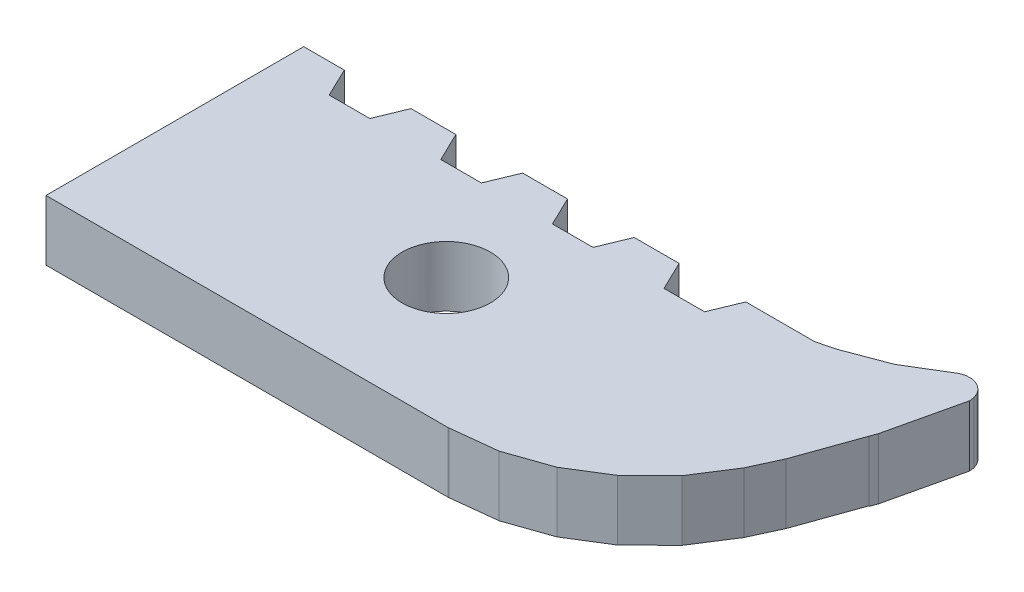
SolidWorks part; units mm, degrees
material "PET"
ref_plane "Front" through (0, 0, 0) normal (0, 0, 1) x (1, 0, 0)
ref_plane "Top" through (0, 0, 0) normal (0, 1, 0) x (1, 0, 0)
ref_plane "Right" through (0, 0, 0) normal (1, 0, 0) x (0, 0, -1)
sketch "Sketch1" plane through (0, 0, 0) normal (0, 1, 0) x (1, 0, 0)
  line L0 (-23.1719, 5.6259) -> (-23.1719, -7.0741)
  line L1 (-23.1719, 5.6259) -> (2.2281, 5.6259)
  line L3 (-23.1719, -7.0741) -> (2.2281, -7.0741)
  line L5 (-23.1719, 5.6259) -> (2.2281, -7.0741) construction
  line L6 (-23.1719, -7.0741) -> (2.2281, 5.6259) construction
  arc A1 (2.2281, 5.6259) -> (2.2281, -7.0741) centre (2.2281, -0.7241) cw
  point P4 (-10.4719, -0.7241)
  dimension "D3" = 12.7
extrude "Boss-Extrude1" add sketch "Sketch1" along normal blind 2.975
sketch "Sketch3" plane through (0, 2.975, 0) normal (0, 1, 0) x (1, 0, 0)
  line L1 (-21.1719, 5.6259) -> (-17.8821, 5.6259)
  line L2 (2.2281, 5.6259) -> (-23.1719, 5.6259) construction
  line L3 (-21.1719, 5.6259) -> (-20.4769, 4.1873)
  line L4 (-20.4769, 4.1873) -> (-18.4769, 4.1873)
  line L5 (-18.4769, 4.1873) -> (-17.8821, 5.6259)
  line L6 (-15.6719, 5.6259) -> (-12.3821, 5.6259)
  line L7 (-10.1719, 5.6259) -> (-6.8821, 5.6259)
  line L8 (-15.6719, 5.6259) -> (-14.9769, 4.1873)
  line L9 (-14.9769, 4.1873) -> (-12.9769, 4.1873)
  line L10 (-12.9769, 4.1873) -> (-12.3821, 5.6259)
  line L11 (-4.6719, 5.6259) -> (-1.3821, 5.6259)
  line L13 (-10.1719, 5.6259) -> (-9.4769, 4.1873)
  line L14 (-9.4769, 4.1873) -> (-7.4769, 4.1873)
  line L15 (-7.4769, 4.1873) -> (-6.8821, 5.6259)
  line L18 (-4.6719, 5.6259) -> (-3.9769, 4.1873)
  line L19 (-3.9769, 4.1873) -> (-1.9769, 4.1873)
  line L20 (-1.9769, 4.1873) -> (-1.3821, 5.6259)
  circle A0 centre (-9.8069, -0.7139) radius 2.175
  line M7 (2.2281, 5.6259) -> (-23.1719, 5.6259)
  dimension "D2" = 4.35
  dimension "D1" = 7.83
  dimension "D5" = 4
  dimension "D6" = 2
extrude "Cut-Extrude1" cut sketch "Sketch3" against normal blind 10 contours L4 L5 L3 M7 | L9 L10 L8 M7 | L14 L15 L13 M7 | L19 L20 L18 M7 | A0
sketch "Sketch4" plane through (0, 2.975, 0) normal (0, 1, 0) x (1, 0, 0)
  line L0 (2.0125, 5.6259) -> (2.8774, 5.8481)
  line L1 (2.2281, 5.6259) -> (-1.3821, 5.6259) construction
  line L2 (2.8774, 5.8481) -> (4.9554, 6.6311)
  line L3 (4.9554, 6.6311) -> (6.9323, 7.8312)
  line L4 (8.349, 6.9213) -> (7.506, 3.2785)
  line L5 (7.506, 3.2785) -> (7.3819, 2.9367)
  line L6 (6.9323, 7.8312) -> (7.181, 7.9079)
  line L7 (7.181, 7.9079) -> (7.4494, 7.9171)
  line L8 (7.4494, 7.9171) -> (7.669, 7.8695)
  line L9 (7.669, 7.8695) -> (7.91, 7.7499)
  line L10 (7.91, 7.7499) -> (8.0903, 7.5933)
  line L11 (8.0903, 7.5933) -> (8.2291, 7.3969)
  line L12 (8.2291, 7.3969) -> (8.3206, 7.1589)
  line L13 (8.3206, 7.1589) -> (8.349, 6.9213)
  line L14 (2.0125, 5.6259) -> (3.6352, 5.468)
  line L15 (3.6352, 5.468) -> (4.9554, 5.0103)
  line L16 (4.9554, 5.0103) -> (6.1883, 4.2396)
  line L18 (6.1883, 4.2396) -> (7.1918, 3.2361)
  line L19 (7.1918, 3.2361) -> (7.3819, 2.9367)
  arc A0 (8.349, 6.9213) -> (6.7466, 7.7203) centre (7.349, 6.9221) ccw construction
  arc A1 (2.2281, -7.0741) -> (2.2281, 5.6259) centre (2.2281, -0.7241) ccw construction
  parabola Q0 (6.7466, 7.7203) -> (1.998, 5.627) focus (4.2184, 12.0645) apex (7.6534, 8.4935) construction
  parabola Q1 (6.7466, 7.7203) -> (1.998, 5.627) focus (4.2184, 12.0645) apex (7.6534, 8.4935) construction
  parabola Q2 (8.349, 6.9213) -> (5.6517, -1.5014) focus (-7.439, 2.8103) apex (3.7093, -4.8211) construction
extrude "Boss-Extrude2" add sketch "Sketch4" against normal blind 3
sketch "Sketch5" plane through (0, 0, 0) normal (0, -1, 0) x (1, 0, 0)
  line L0 (7.3819, -2.9367) -> (6.3076, 0.0762)
  line L1 (6.3076, 0.0762) -> (5.6517, 1.5014)
  line L2 (5.6517, 1.5014) -> (4.4638, 3.3564)
  line L3 (4.4638, 3.3564) -> (2.8629, 4.9344)
  line L4 (2.8629, 4.9344) -> (1.0192, 6.0821)
  line L5 (1.0192, 6.0821) -> (-1.0928, 6.8195)
  line L6 (-1.0928, 6.8195) -> (-3.3217, 7.0689)
  line L7 (-3.3217, 7.0689) -> (2.2281, 7.0741)
  line L8 (2.2281, 7.0741) -> (3.7603, 6.8865)
  line L9 (3.7603, 6.8865) -> (5.2045, 6.3334)
  line L10 (5.2045, 6.3334) -> (6.4816, 5.439)
  line L11 (6.4816, 5.439) -> (7.4841, 4.2874)
  line L12 (7.4841, 4.2874) -> (8.1885, 2.9141)
  line L13 (8.1885, 2.9141) -> (8.5435, 1.3858)
  line L14 (8.5435, 1.3858) -> (8.5214, -0.1227)
  line L15 (8.5214, -0.1227) -> (8.1237, -1.6347)
  line L18 (7.3936, -2.9691) -> (8.1237, -1.6347)
  line L19 (7.3936, -2.9691) -> (7.3819, -2.9367)
  arc A0 (5.6517, 1.5014) -> (-3.32, 7.0689) centre (-3.3123, -2.9311) ccw construction
  arc A1 (7.3936, -2.9691) -> (2.2281, 7.0741) centre (2.2281, 0.7241) ccw construction
  parabola Q0 (8.349, -6.9213) -> (5.6517, 1.5014) focus (-7.439, -2.8103) apex (3.7093, 4.8211) construction
extrude "Cut-Extrude4" cut sketch "Sketch5" against normal blind 3 contours L15 L18 L19 L0 L1 L2 L3 L4 L5 L6 L7 L8 L9 L10 L11 L12 L13 L14
sketch "Sketch8" plane through (0, 0, 0) normal (0, -1, 0) x (1, 0, 0)
  line L0 (7.3936, -2.9691) -> (4.8173, 7.1783)
  line L7 (4.8173, 7.1783) -> (13.1491, 1.2596)
  line L8 (13.1491, 1.2596) -> (7.3936, -2.9691)
extrude "Cut-Extrude5" cut sketch "Sketch8" against normal blind 3 contours L7 L8 L0
sketch "Sketch9" plane through (0, 2.975, 0) normal (0, 1, 0) x (1, 0, 0)
  line L2 (-2.8127, -7.2106) -> (5.0272, -8.632)
  line L3 (5.0272, -8.632) -> (5.5042, -6.001)
  line L4 (5.5042, -6.001) -> (-2.8127, -7.2106)
extrude "Cut-Extrude6" cut sketch "Sketch9" against normal blind 3
sketch "Sketch10" plane through (0, 2.975, 0) normal (0, 1, 0) x (1, 0, 0)
  line L0 (-3.3217, -7.0689) -> (-3.3538, -7.0741)
  line L1 (-23.1719, -7.0741) -> (-1.8742, -7.0741) construction
  line L2 (-3.3538, -7.0741) -> (-1.9005, -7.1442)
  line L3 (-1.9005, -7.1442) -> (-1.7552, -7.0123)
  line L4 (-1.7552, -7.0123) -> (-3.3217, -7.0689)
extrude "Cut-Extrude7" cut sketch "Sketch10" against normal blind 3
